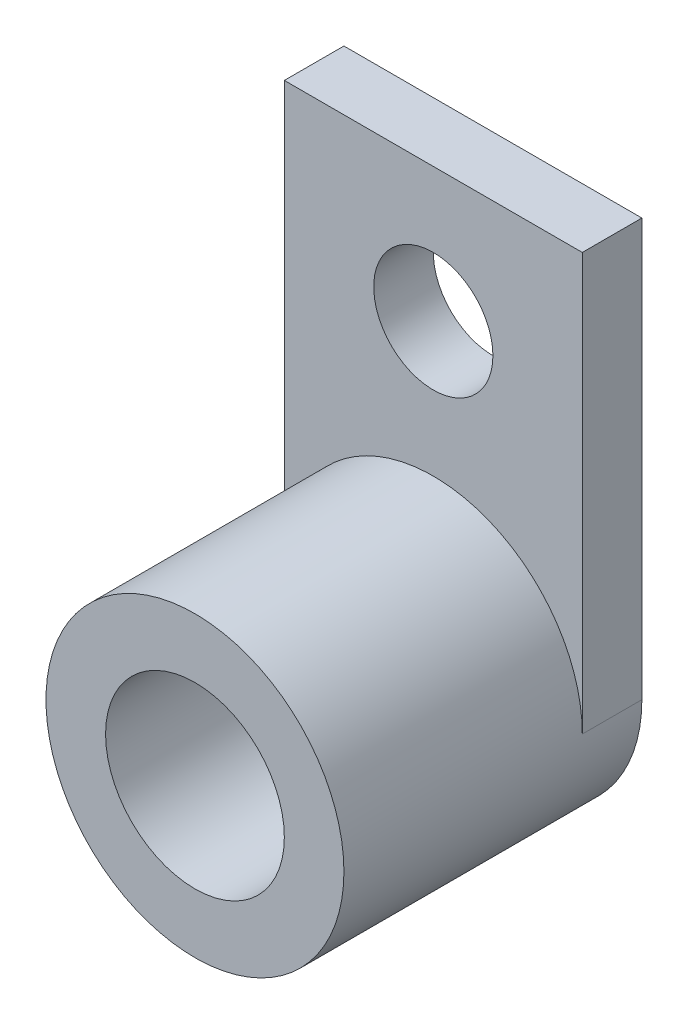
SolidWorks part; units mm, degrees
ref_plane "Front Plane" through (0, 0, 0) normal (1, 0, 0) x (0, 1, 0)
ref_plane "Top Plane" through (0, 0, 0) normal (0, 0, 1) x (0, 1, 0)
ref_plane "Right Plane" through (0, 0, 0) normal (0, 1, 0) x (-1, 0, 0)
sketch "Sketch3" plane through (0, 0, 0) normal (0, 0, 1) x (0, 1, 0)
  circle A0 centre (0, 0) radius 63.5
  circle A1 centre (0, 0) radius 38.1
  dimension "D1" = 127
  dimension "D2" = 76.2
extrude "Boss-Extrude1" add sketch "Sketch3" along normal blind 127
sketch "Sketch4" plane through (0, 0, 0) normal (0, 0, 1) x (0, 1, 0)
  line L1 (0, 63.5) -> (177.8, 63.5)
  line L2 (0, -63.5) -> (177.8, -63.5)
  line L3 (177.8, 63.5) -> (177.8, -63.5)
  line L4 (0, -69.85) -> (0, 69.85) construction
  line L5 (-69.85, 0) -> (69.85, 0) construction
  circle A0 centre (0, 0) radius 63.5 construction
  arc A1 (0, 63.5) -> (0, -63.5) centre (0, 0) ccw
  circle A2 centre (0, 0) radius 38.1 construction
  circle A3 centre (0, 0) radius 38.1
  circle A4 centre (120.65, 0) radius 25.4
  point P2 (0, 0)
  dimension "D2" = 50.8
  dimension "D1" = 177.8
  dimension "D3" = 57.15
extrude "Boss-Extrude2" add sketch "Sketch4" along normal blind 25.4
